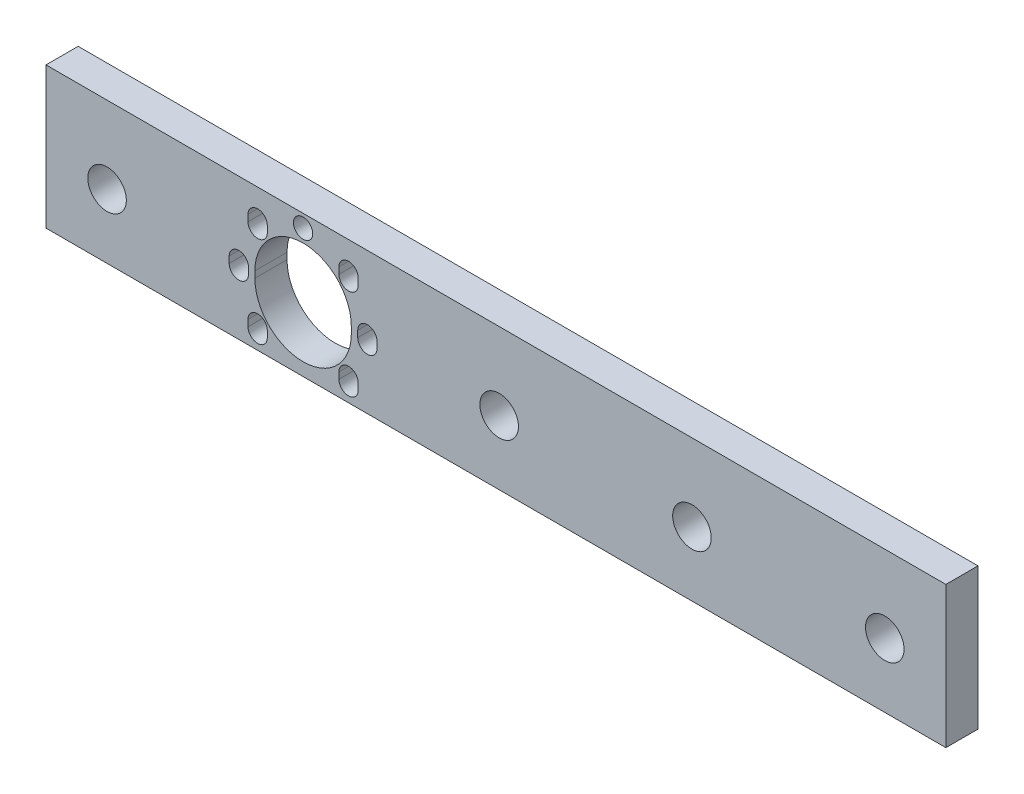
SolidWorks part; units mm, degrees
ref_plane "정면" through (0, 0, 0) normal (0, 0, 1) x (1, 0, 0)
ref_plane "윗면" through (0, 0, 0) normal (0, 1, 0) x (1, 0, 0)
ref_plane "우측면" through (0, 0, 0) normal (1, 0, 0) x (0, 0, -1)
sketch "스케치1" plane through (0, 0, 0) normal (0, 0, 1) x (1, 0, 0)
  line L0 (0, 10.1) -> (0, 0.1)
  line L1 (0, 10.1) -> (0, 22.1)
  line L2 (0, 22.1) -> (140, 22.1)
  line L3 (140, 22.1) -> (140, 10.1)
  line L4 (-0.1356, 10.1) -> (139.8644, 10.1) construction
  line L5 (0, 10.1) -> (10, 10.1) construction
  line L6 (10, 10.1) -> (40, 10.1) construction
  line L7 (40, 10.1) -> (70.5, 10.1) construction
  line L8 (70.5, 10.1) -> (100.5, 10.1) construction
  line L9 (100.5, 10.1) -> (130.5, 10.1) construction
  line L10 (0, 0.1) -> (140, 0.1)
  line L11 (140, 10.1) -> (140, 0.1)
  line L12 (0, 10.1) -> (9.5, 10.1)
  line L13 (32.5, 10.1) -> (32.5, 10.6)
  line L14 (32.5, 10.1) -> (32.5, 9.6)
  line L15 (40, 10.1) -> (40, 25.5279) construction
  line L16 (47.5, 10.1) -> (47.5, 9.6)
  line L17 (47.5, 10.1) -> (47.5, 10.6)
  line L18 (32.5, 10.6) -> (47.5, 10.6) construction
  line L19 (40, 10.6) -> (40, 18.1)
  line L20 (31.4289, 3.0289) -> (31.4289, 3.5289)
  line L21 (32.9289, 3.0289) -> (32.9289, 1.5289) construction
  line L22 (31.4289, 3.0289) -> (31.4289, 2.5289)
  line L23 (34.4289, 3.0289) -> (34.4289, 3.5289)
  line L24 (34.4289, 3.0289) -> (34.4289, 2.5289)
  line L25 (31.4289, 3.5289) -> (34.4289, 3.5289) construction
  line L26 (32.9289, 3.5289) -> (32.9289, 5.0289) construction
  line L27 (31.4289, 3.0289) -> (34.4289, 3.0289) construction
  line L28 (28.5, 10.1) -> (28.5, 10.6)
  line L29 (28.5, 10.1) -> (28.5, 9.6)
  line L30 (30, 10.1) -> (30, 11.6) construction
  line L31 (31.5, 10.1) -> (31.5, 9.6)
  line L32 (31.5, 10.1) -> (31.5, 10.6)
  line L33 (28.5, 10.6) -> (31.5, 10.6) construction
  line L34 (30, 10.6) -> (30, 12.6) construction
  line L35 (31.4289, 17.1711) -> (31.4289, 17.6711)
  line L36 (31.4289, 17.1711) -> (31.4289, 16.6711)
  line L37 (31.4289, 17.1711) -> (34.4289, 17.1711) construction
  line L38 (34.4289, 17.1711) -> (34.4289, 17.6711)
  line L39 (34.4289, 17.1711) -> (34.4289, 16.6711)
  line L40 (31.4289, 17.6711) -> (34.4289, 17.6711) construction
  line L41 (32.9289, 17.6711) -> (32.9289, 19.1711) construction
  line L42 (45.5711, 17.1711) -> (45.5711, 16.6711)
  line L43 (45.5711, 17.1711) -> (45.5711, 17.6711)
  line L44 (48.5711, 17.1711) -> (48.5711, 17.6711)
  line L45 (48.5711, 17.1711) -> (48.5711, 16.6711)
  line L46 (51.5, 10.1) -> (51.5, 9.6)
  line L47 (51.5, 10.1) -> (51.5, 10.6)
  line L48 (48.5, 10.1) -> (48.5, 10.6)
  line L49 (48.5, 10.1) -> (48.5, 9.6)
  line L50 (48.5711, 3.0289) -> (48.5711, 3.5289)
  line L51 (45.5711, 3.0289) -> (45.5711, 3.5289)
  line L52 (45.5711, 3.0289) -> (45.5711, 2.5289)
  line L53 (48.5711, 3.0289) -> (48.5711, 2.5289)
  arc A0 (32.5, 10.6) -> (47.5, 10.6) centre (40, 10.6) cw
  circle A1 centre (40, 10.1) radius 10 construction
  circle A5 centre (40, 20.1) radius 1.5
  arc A6 (48.5711, 17.6711) -> (45.5711, 17.6711) centre (47.0711, 17.6711) ccw
  arc A7 (48.5711, 16.6711) -> (45.5711, 16.6711) centre (47.0711, 16.6711) cw
  arc A8 (51.5, 10.6) -> (48.5, 10.6) centre (50, 10.6) ccw
  arc A9 (32.5, 9.6) -> (47.5, 9.6) centre (40, 9.6) ccw
  circle A11 centre (70.5, 10.1) radius 3
  circle A12 centre (100.5, 10.1) radius 3
  circle A13 centre (130.5, 10.1) radius 3
  arc A14 (31.4289, 3.5289) -> (34.4289, 3.5289) centre (32.9289, 3.5289) cw
  circle A15 centre (9.5, 10.1) radius 3
  arc A17 (31.4289, 2.5289) -> (34.4289, 2.5289) centre (32.9289, 2.5289) ccw
  arc A18 (28.5, 10.6) -> (31.5, 10.6) centre (30, 10.6) cw
  arc A19 (28.5, 9.6) -> (31.5, 9.6) centre (30, 9.6) ccw
  arc A20 (31.4289, 17.6711) -> (34.4289, 17.6711) centre (32.9289, 17.6711) cw
  arc A21 (31.4289, 16.6711) -> (34.4289, 16.6711) centre (32.9289, 16.6711) ccw
  arc A25 (51.5, 9.6) -> (48.5, 9.6) centre (50, 9.6) cw
  arc A26 (48.5711, 3.5289) -> (45.5711, 3.5289) centre (47.0711, 3.5289) ccw
  arc A27 (48.5711, 2.5289) -> (45.5711, 2.5289) centre (47.0711, 2.5289) cw
  point P33 (40, 10.1)
  dimension "D1" = 30.5
  dimension "D7" = 10
  dimension "D3" = 9.5
  dimension "D4" = 30.5
  dimension "D5" = 30
  dimension "D6" = 30
extrude "보스-돌출1" add sketch "스케치1" along normal blind 5 contours A15 | L1 L2 L3 L11 L10 L0 | A5 | A9 L16 L17 A0 L13 L14 | A11 | A12 | A13 | A7 L42 L43 A6 L44 L45 | A14 L23 L24 A17 L22 L20 | A20 L38 L39 A21 L36 L35 | L31 A19 L29 L28 A18 L32 | A25 L49 L48 A8 L47 L46 | L51 A26 L50 L53 A27 L52
